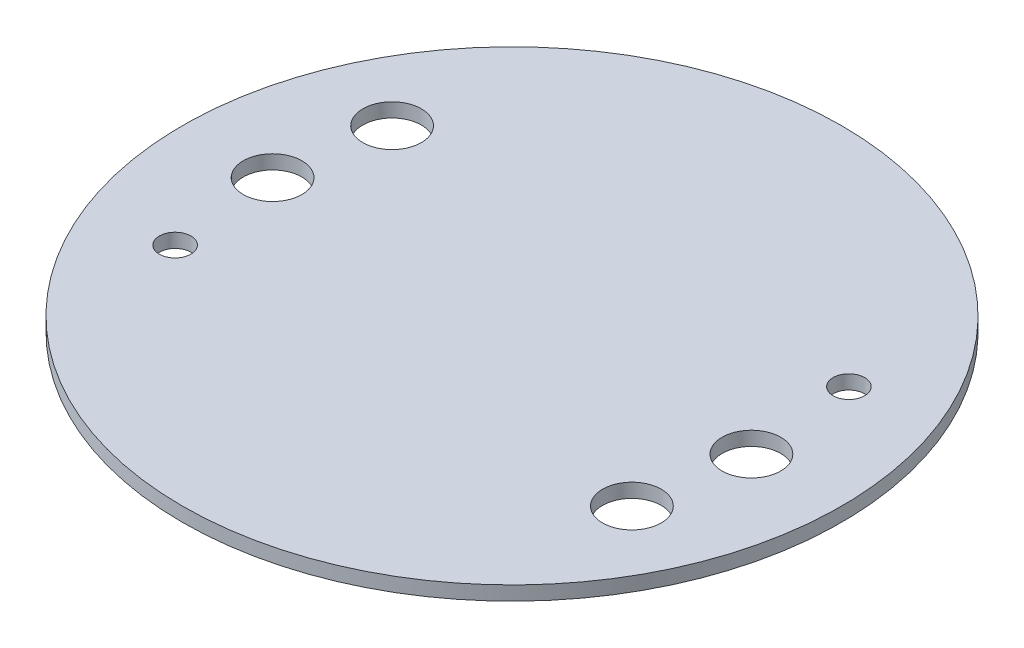
SolidWorks part; units mm, degrees
ref_plane "Front Plane" through (0, 0, 0) normal (0, 0, 1) x (1, 0, 0)
ref_plane "Top Plane" through (0, 0, 0) normal (0, 1, 0) x (1, 0, 0)
ref_plane "Right Plane" through (0, 0, 0) normal (1, 0, 0) x (0, 0, -1)
sketch "Sketch1" plane through (0, 0, 0) normal (0, 1, 0) x (1, 0, 0)
  circle A0 centre (0, 0) radius 74.295
extrude "Boss-Extrude1" add sketch "Sketch1" along normal blind 3.175
sketch "Sketch2" plane through (0, 3.175, 0) normal (0, 1, 0) x (1, 0, 0)
  line L0 (53.975, 0) -> (-53.975, 0) construction
  line L1 (51.7955, 24.1526) -> (-51.7955, -24.1526)
  line L2 (0, 0) -> (50.6445, -23.6159) construction
  line L3 (0, 0) -> (-50.6445, 23.6159) construction
  circle A0 centre (-53.975, 0) radius 6.604
  circle A1 centre (53.975, 0) radius 6.604
  circle A2 centre (-51.7955, -24.1526) radius 3.556
  circle A3 centre (51.7955, 24.1526) radius 3.556
  circle A4 centre (50.6445, -23.6159) radius 6.604
  circle A5 centre (-50.6445, 23.6159) radius 6.604
  point P4 (0, 0)
  point P10 (0, 0)
extrude "Cut-Extrude1" cut sketch "Sketch2" against normal blind 3.175
